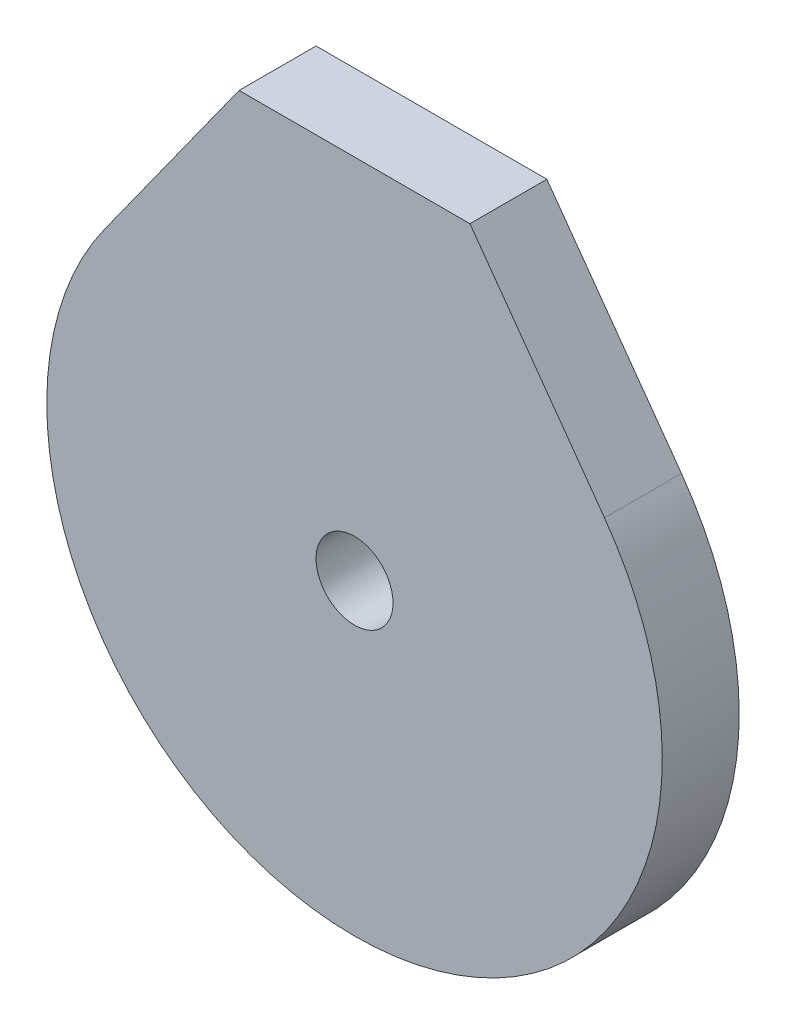
SolidWorks part; units mm, degrees
ref_plane "Front Plane" through (0, 0, 0) normal (0, 0, 1) x (1, 0, 0)
ref_plane "Top Plane" through (0, 0, 0) normal (0, 1, 0) x (1, 0, 0)
ref_plane "Right Plane" through (0, 0, 0) normal (1, 0, 0) x (0, 0, -1)
sketch "Sketch1" plane through (0, 0, 0) normal (0, 0, 1) x (1, 0, 0)
  line L0 (-32.4945, 23.3261) -> (-15, 47.697)
  line L1 (-15, 47.697) -> (15, 47.697)
  line L2 (15, 47.697) -> (32.4945, 23.3261)
  arc A0 (-32.4945, 23.3261) -> (32.4945, 23.3261) centre (0, 0) ccw
  circle A1 centre (0, 0) radius 5
  point P8 (0, 47.697)
  dimension "D1" = 80
  dimension "D2" = 10
  dimension "D3" = 30
  dimension "D4" = 30
extrude "Boss-Extrude1" add sketch "Sketch1" along normal mid plane 10
